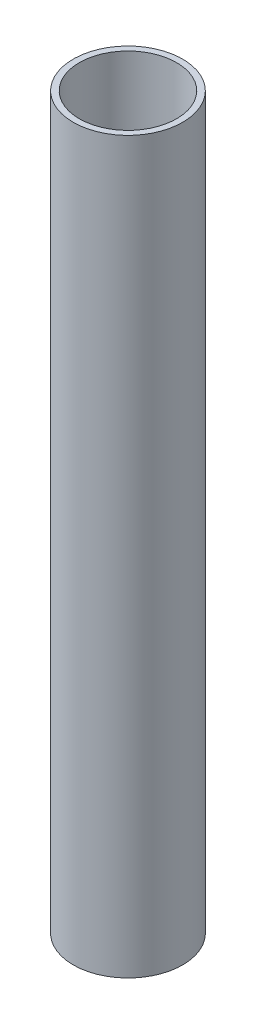
SolidWorks part; units mm, degrees
ref_plane "前视基准面" through (0, 0, 0) normal (0, 0, 1) x (1, 0, 0)
ref_plane "上视基准面" through (0, 0, 0) normal (0, 1, 0) x (1, 0, 0)
ref_plane "右视基准面" through (0, 0, 0) normal (1, 0, 0) x (0, 0, -1)
other "Configuration Table"
sketch "草图1" plane through (0, 0, 0) normal (0, 1, 0) x (1, 0, 0)
  circle A0 centre (0, 0) radius 8
  circle A1 centre (0, 0) radius 9
  dimension "D1" = 16
  dimension "D2" = 18
extrude "凸台-拉伸1" add sketch "草图1" along normal blind 120
